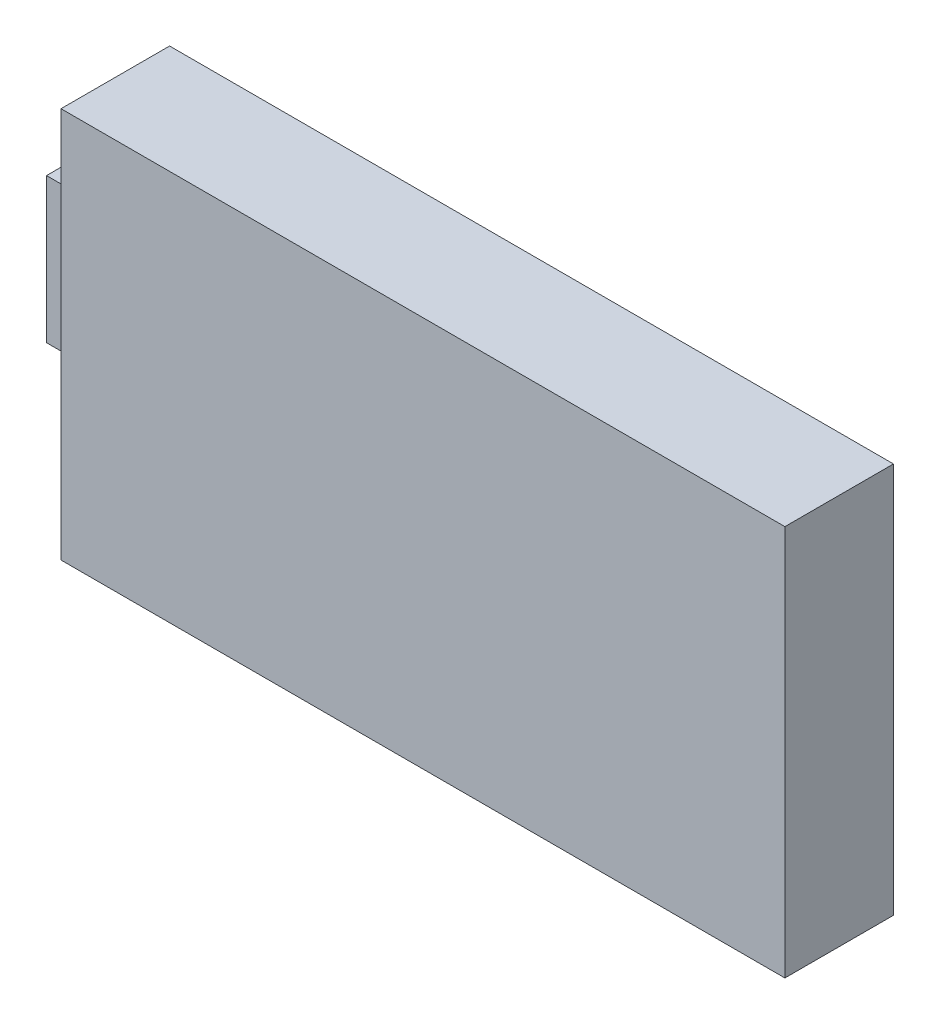
SolidWorks part; units mm, degrees
ref_plane "Front Plane" through (0, 0, 0) normal (0, 0, 1) x (1, 0, 0)
ref_plane "Top Plane" through (0, 0, 0) normal (0, 1, 0) x (1, 0, 0)
ref_plane "Right Plane" through (0, 0, 0) normal (1, 0, 0) x (0, 0, -1)
sketch "Sketch1" plane through (0, 0, 0) normal (0, 0, 1) x (1, 0, 0)
  line L1 (-25, 13.5) -> (25, 13.5)
  line L2 (-25, 13.5) -> (-25, -13.5)
  line L3 (-25, -13.5) -> (25, -13.5)
  line L4 (25, 13.5) -> (25, -13.5)
  line L5 (-25, 13.5) -> (25, -13.5) construction
  line L6 (-25, -13.5) -> (25, 13.5) construction
  point P0 (0, 0)
  dimension "D1" = 27
  dimension "D2" = 50
extrude "Boss-Extrude1" add sketch "Sketch1" along normal blind 7.5
sketch "Sketch2" plane through (-25, 0, 0) normal (-1, 0, 0) x (0, 0, 1)
  line L0 (0, 13.5) -> (0, -13.5) construction
  line L1 (0, 5) -> (3.5, 5)
  line L2 (0, 5) -> (0, -5)
  line L3 (0, -5) -> (3.5, -5)
  line L4 (3.5, 5) -> (3.5, -5)
  dimension "D1" = 3.5
  dimension "D2" = 10
extrude "Boss-Extrude2" add sketch "Sketch2" along normal blind 5
